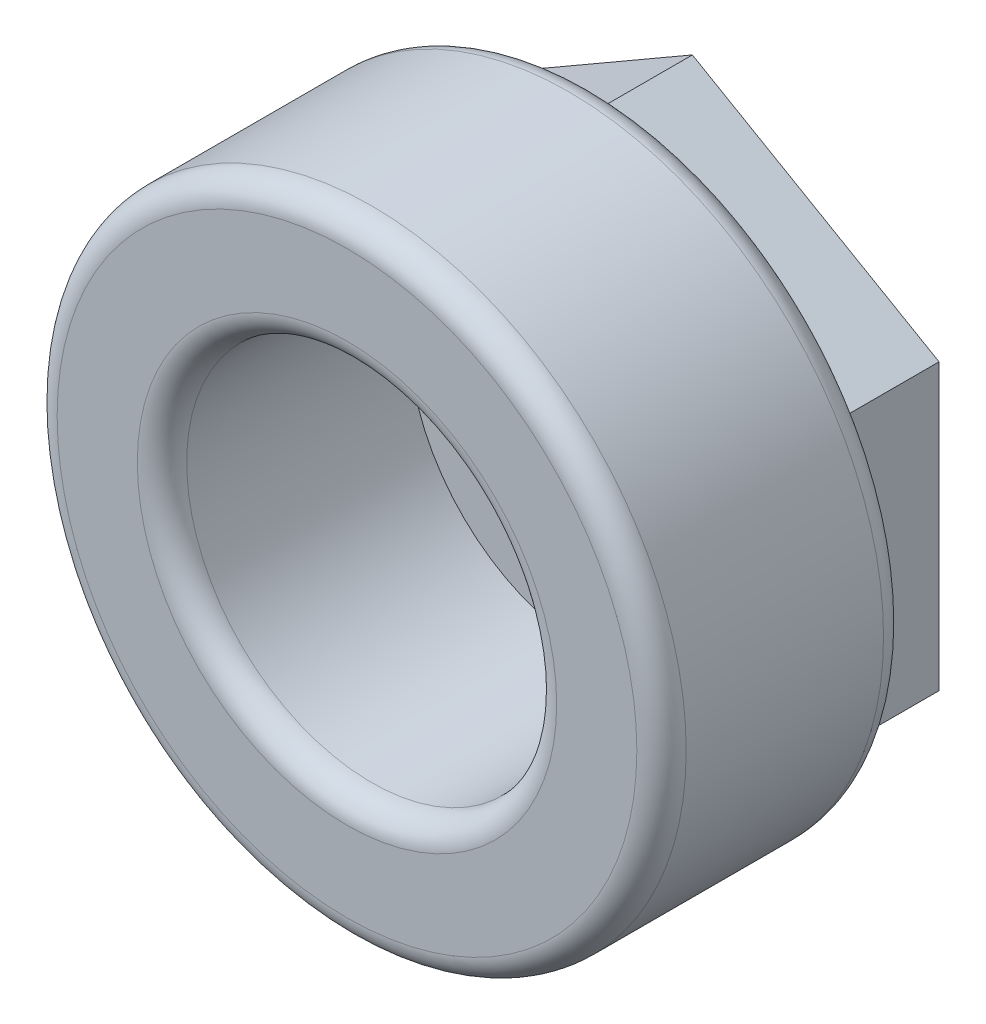
SolidWorks part; units mm, degrees
ref_plane "前视基准面" through (0, 0, 0) normal (0, 0, 1) x (1, 0, 0)
ref_plane "上视基准面" through (0, 0, 0) normal (0, 1, 0) x (1, 0, 0)
ref_plane "右视基准面" through (0, 0, 0) normal (1, 0, 0) x (0, 0, -1)
sketch "草图1" plane through (0, 0, 0) normal (0, 0, 1) x (1, 0, 0)
  line L1 (0, -2.3094) -> (2, -1.1547)
  line L2 (2, -1.1547) -> (2, 1.1547)
  line L3 (2, 1.1547) -> (0, 2.3094)
  line L4 (0, 2.3094) -> (-2, 1.1547)
  line L5 (-2, 1.1547) -> (-2, -1.1547)
  line L6 (-2, -1.1547) -> (0, -2.3094)
  circle A0 centre (0, 0) radius 2 construction
  dimension "D1" = 4
extrude "凸台-拉伸1" add sketch "草图1" along normal blind 0.8
sketch "草图2" plane through (0, 0, 0.8) normal (0, 0, 1) x (1, 0, 0)
  circle A0 centre (0, 0) radius 2.55
  circle A1 centre (0, 0) radius 1.5
  dimension "D1" = 3
  dimension "D2" = 5.1
extrude "凸台-拉伸2" add sketch "草图2" along normal blind 2
sketch "草图3" plane through (0, 0, 0.8) normal (0, 0, 1) x (1, 0, 0)
  circle A0 centre (0, 0) radius 1
  dimension "D1" = 2
extrude "切除-拉伸1" cut sketch "草图3" against normal through all
fillet "圆角1" radius 0.2 3 edges at (2.55, 0, 2.8) (1.5, 0, 2.8) (2.55, 0, 0.8)
